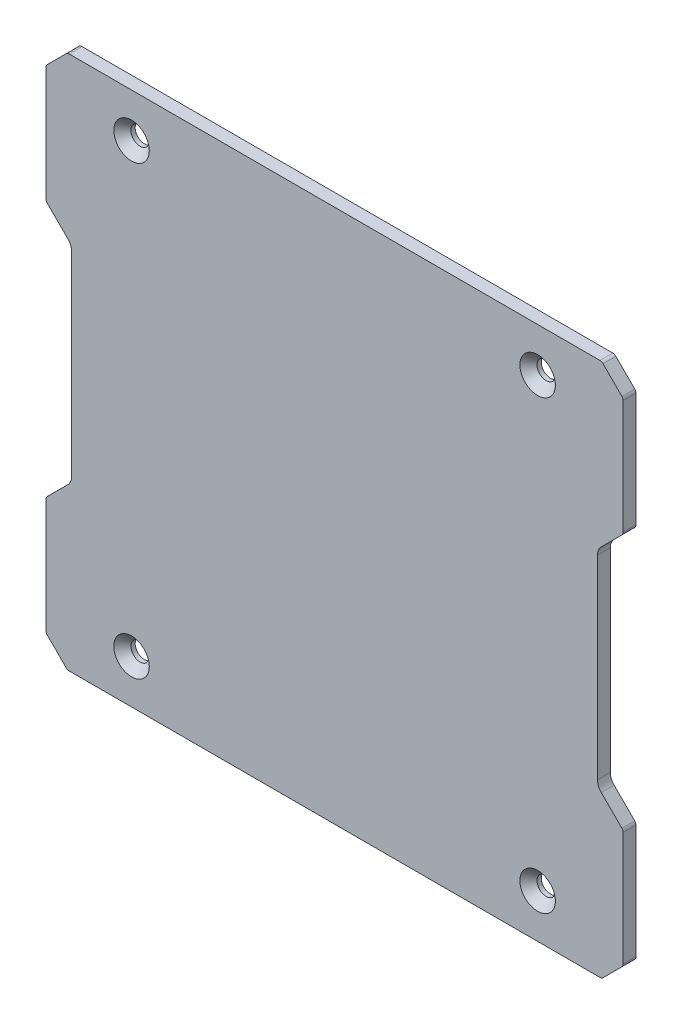
SolidWorks part; units mm, degrees
ref_plane "前视基准面" through (0, 0, 0) normal (0, 0, 1) x (1, 0, 0)
ref_plane "上视基准面" through (0, 0, 0) normal (0, 1, 0) x (1, 0, 0)
ref_plane "右视基准面" through (0, 0, 0) normal (1, 0, 0) x (0, 0, -1)
sketch "草图1" plane through (0, 0, 0) normal (0, 0, 1) x (1, 0, 0)
  line L0 (-61.5, 39.7426) -> (61.5, 39.7426) construction
  line L1 (-67.5, 5.4142) -> (67.5, 5.4142) construction
  line L2 (61.796, 125) -> (63.9459, 125) construction
  line L3 (63.9851, 123.5149) -> (-35291.3539, 35478.8539) construction
  line L4 (62.5, 125) -> (67.5, 120) construction
  line L5 (62.3787, 87.3787) -> (-62.3787, 87.3787) construction
  line L6 (-61.5, 62.5) -> (-47.5, 62.5) construction
  line L7 (-47.5, 10.25) -> (47.5, 10.25) construction
  line L8 (-47.5, 10.25) -> (-47.5, 114.75) construction
  line L9 (-47.5, 114.75) -> (47.5, 114.75) construction
  line L10 (47.5, 10.25) -> (47.5, 114.75) construction
  line L32 (-61.5, 85.2574) -> (-61.5, 39.7426)
  line L33 (-62.3787, 37.6213) -> (-67.2071, 32.7929)
  line L34 (-67.5, 32.0858) -> (-67.5, 5.4142)
  line L35 (-67.2071, 4.7071) -> (-62.7929, 0.2929)
  line L36 (-62.0858, 0) -> (62.0858, 0)
  line L37 (62.7929, 0.2929) -> (67.2071, 4.7071)
  line L38 (67.5, 5.4142) -> (67.5, 32.0858)
  line L39 (67.2071, 32.7929) -> (62.3787, 37.6213)
  line L40 (61.5, 39.7426) -> (61.5, 85.2574)
  line L41 (62.3787, 87.3787) -> (67.2071, 92.2071)
  line L42 (67.5, 92.9142) -> (67.5, 119.5858)
  line L43 (67.2071, 120.2929) -> (62.7929, 124.7071)
  line L44 (62.0858, 125) -> (-62.0858, 125)
  line L45 (-62.7929, 124.7071) -> (-67.2071, 120.2929)
  line L46 (-67.5, 119.5858) -> (-67.5, 92.9142)
  line L47 (-67.2071, 92.2071) -> (-62.3787, 87.3787)
  circle A0 centre (47.5, 10.25) radius 2.15
  circle A1 centre (-47.5, 10.25) radius 2.15
  circle A2 centre (-47.5, 114.75) radius 2.15
  circle A3 centre (47.5, 114.75) radius 2.15
  arc A32 (-61.5, 85.2574) -> (-62.3787, 87.3787) centre (-64.5, 85.2574) ccw
  arc A33 (-62.3787, 37.6213) -> (-61.5, 39.7426) centre (-64.5, 39.7426) ccw
  arc A34 (-67.2071, 32.7929) -> (-67.5, 32.0858) centre (-66.5, 32.0858) ccw
  arc A35 (-67.5, 5.4142) -> (-67.2071, 4.7071) centre (-66.5, 5.4142) ccw
  arc A36 (-62.7929, 0.2929) -> (-62.0858, 0) centre (-62.0858, 1) ccw
  arc A37 (62.0858, 0) -> (62.7929, 0.2929) centre (62.0858, 1) ccw
  arc A38 (67.2071, 4.7071) -> (67.5, 5.4142) centre (66.5, 5.4142) ccw
  arc A39 (67.5, 32.0858) -> (67.2071, 32.7929) centre (66.5, 32.0858) ccw
  arc A40 (61.5, 39.7426) -> (62.3787, 37.6213) centre (64.5, 39.7426) ccw
  arc A41 (62.3787, 87.3787) -> (61.5, 85.2574) centre (64.5, 85.2574) ccw
  arc A42 (67.2071, 92.2071) -> (67.5, 92.9142) centre (66.5, 92.9142) ccw
  arc A43 (67.5, 119.5858) -> (67.2071, 120.2929) centre (66.5, 119.5858) ccw
  arc A44 (62.7929, 124.7071) -> (62.0858, 125) centre (62.0858, 124) ccw
  arc A45 (-62.0858, 125) -> (-62.7929, 124.7071) centre (-62.0858, 124) ccw
  arc A46 (-67.2071, 120.2929) -> (-67.5, 119.5858) centre (-66.5, 119.5858) ccw
  arc A47 (-67.5, 92.9142) -> (-67.2071, 92.2071) centre (-66.5, 92.9142) ccw
  point P40 (0, 10.25)
  point P48 (0, 0)
  point P50 (0, 125)
  point P51 (0, 39.7426)
  point P53 (0, 5.4142)
  dimension "D1" = 135
  dimension "D2" = 125
  dimension "D3" = 123
  dimension "D4" = 104.5
  dimension "D8" = 1
  dimension "D14" = 3
  dimension "D15" = 1
  dimension "D7" = 4.3
  dimension "D5" = 95
  dimension "D9" = 45
  dimension "D10" = 45
  dimension "D11" = 45
  dimension "D12" = 5
  dimension "D13" = 45
  dimension "D16" = 45
  dimension "D17" = 39.7426
  dimension "D18" = 45
  dimension "D19" = 45
  dimension "D20" = 37.6213
  dimension "D21" = 45
extrude "凸台-拉伸1" add sketch "草图1" along normal blind 3
chamfer "倒角1" distance 2 angle 45 4 edges at (-45.35, 114.75, 3) (-45.35, 10.25, 3) (49.65, 10.25, 3) (49.65, 114.75, 3)
